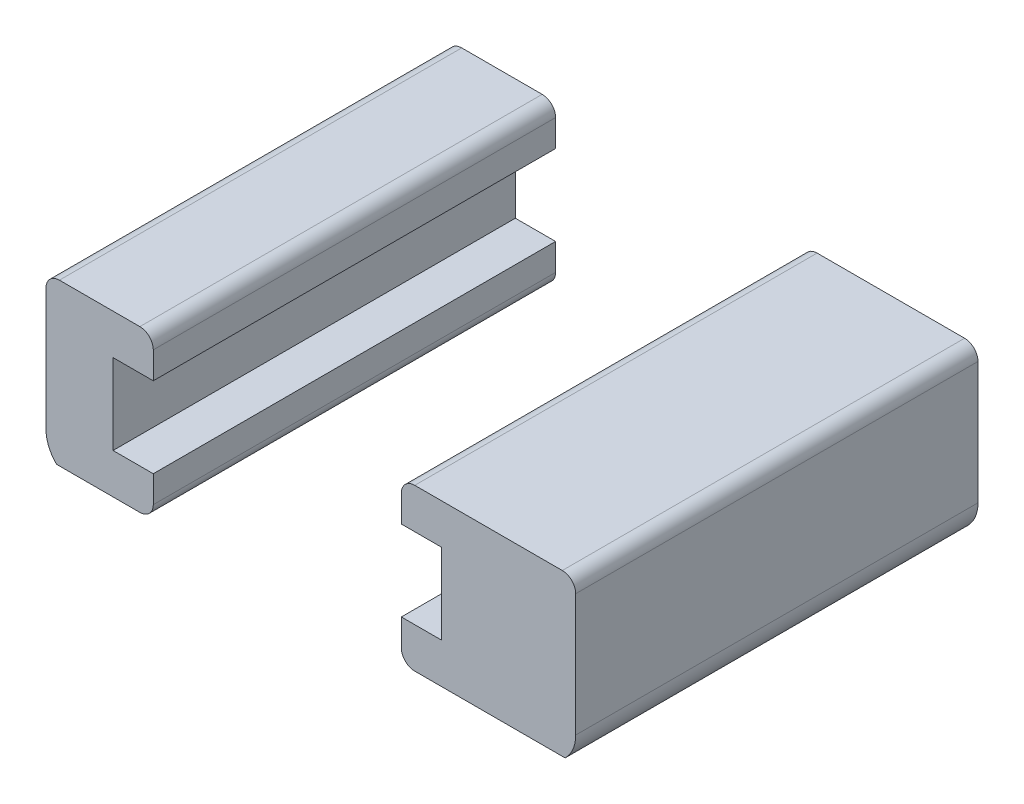
SolidWorks part; units mm, degrees
ref_plane "Front Plane" through (0, 0, 0) normal (0, 0, 1) x (1, 0, 0)
ref_plane "Top Plane" through (0, 0, 0) normal (0, 1, 0) x (1, 0, 0)
ref_plane "Right Plane" through (0, 0, 0) normal (1, 0, 0) x (0, 0, -1)
sketch "Sketch1" plane through (0, 0, 0) normal (0, 0, 1) x (1, 0, 0)
  line L0 (18.5, 18) -> (44.5, 18)
  line L2 (-24.5, 12) -> (-24.5, 0) construction
  line L3 (-24.5, 0) -> (-18.5, 0) construction
  line L4 (24.5, 12) -> (24.5, 0) construction
  line L6 (-34.5, 18) -> (-34.5, -6)
  line L7 (-34.5, -6) -> (-18.5, -6)
  line L8 (44.5, 18) -> (44.5, -6)
  line L10 (-24.5, 12) -> (-24.5, 0)
  line L11 (-24.5, 0) -> (-18.5, 0)
  line L12 (24.5, 12) -> (24.5, 0)
  line L13 (18.5, 0) -> (24.5, 0) construction
  line L15 (-18.5, 0) -> (-18.5, -6)
  line L17 (18.5, 0) -> (18.5, -6)
  line L18 (18.5, 0) -> (24.5, 0)
  line L19 (18.5, -6) -> (44.5, -6)
  line L20 (-18.5, 0) -> (18.5, 0) construction
  line L22 (-34.5, 18) -> (-18.5, 18)
  line L24 (-24.5, 12) -> (-18.5, 12)
  line L25 (-18.5, 18) -> (-18.5, 12)
  line L28 (24.5, 12) -> (18.5, 12)
  line L29 (18.5, 18) -> (18.5, 12)
  point P4 (0, 0)
  dimension "D1" = 12
  dimension "D2" = 49
  dimension "D3" = 6
  dimension "D4" = 6
  dimension "D5" = 20
  dimension "D6" = 6
  dimension "D7" = 10
extrude "Boss-Extrude1" add sketch "Sketch1" along normal mid plane 60
fillet "Fillet1" radius 2 3 edges at (-18.5, -6, 0) (-34.5, 18, 0) (-18.5, 18, 0)
fillet "Fillet2" radius 2 3 edges at (18.5, -6, 0) (44.5, 18, 0) (18.5, 18, 0)
sketch "Sketch2" plane through (0, 0, -30) normal (0, 0, -1) x (-1, 0, 0)
  line L0 (-44.5, -2.2562) -> (-44.5, -6)
  line L1 (-44.5, -6) -> (-42.92, -6)
  line L2 (32.92, -6) -> (34.5, -6)
  line L3 (34.5, -6) -> (34.5, -2.2562)
  ellipse E0 centre (-39.5, -2.2562) end of major axis (-39.5, -7.3883) minor radius 5 (-44.5, -2.2562) -> (-42.92, -6) ccw construction
  ellipse E1 centre (29.5, -2.2562) end of major axis (29.5, 2.8759) minor radius 5 (32.92, -6) -> (34.5, -2.2562) ccw construction
  ellipse E2 centre (-39.5, -2.2562) end of major axis (-39.5, -7.3883) minor radius 5 (-44.5, -2.2562) -> (-42.92, -6) ccw
  ellipse E3 centre (29.5, -2.2562) end of major axis (29.5, 2.8759) minor radius 5 (32.92, -6) -> (34.5, -2.2562) ccw
extrude "Cut-Extrude1" cut sketch "Sketch2" against normal through all both and the other way through all
